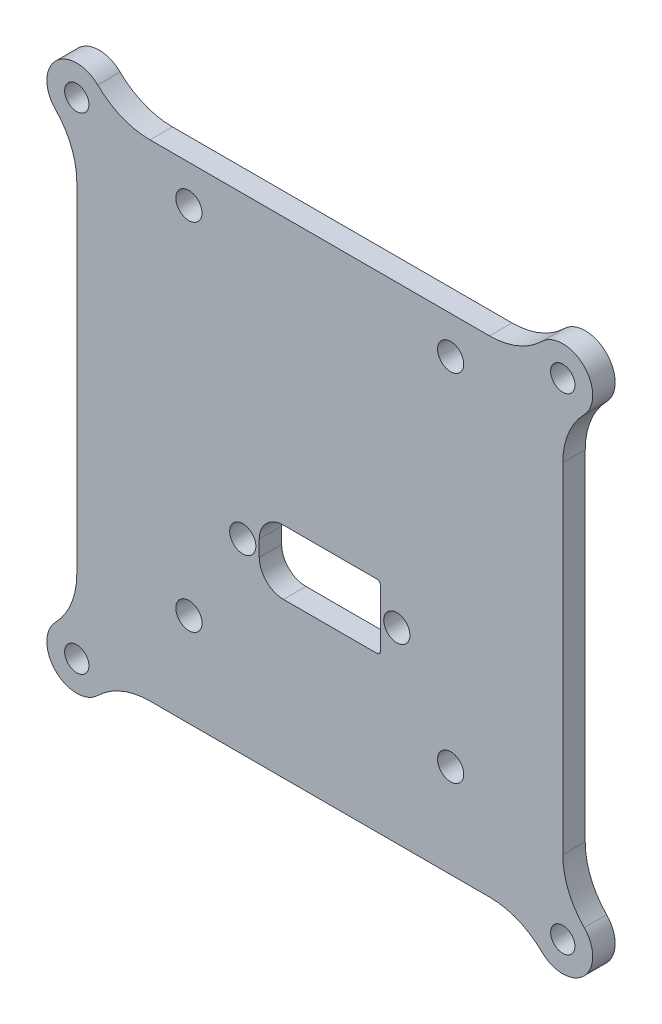
SolidWorks part; units mm, degrees
material "ABS"
ref_plane "Спереди" through (0, 0, 0) normal (0, 0, 1) x (1, 0, 0)
ref_plane "Сверху" through (0, 0, 0) normal (0, 1, 0) x (1, 0, 0)
ref_plane "Справа" through (0, 0, 0) normal (1, 0, 0) x (0, 0, -1)
sketch "Эскиз1" plane through (0, 0, 0) normal (0, 0, 1) x (1, 0, 0)
  line L1 (-32.5, -32.5) -> (32.5, -32.5)
  line L2 (-32.5, -32.5) -> (-32.5, 32.5)
  line L3 (-32.5, 32.5) -> (32.5, 32.5)
  line L4 (32.5, -32.5) -> (32.5, 32.5)
  line L5 (-32.5, -32.5) -> (32.5, 32.5) construction
  line L6 (-32.5, 32.5) -> (32.5, -32.5) construction
  circle A0 centre (-32.5, 32.5) radius 1.625
  arc A1 (-28.5, 32.5) -> (-32.5, 28.5) centre (-32.5, 32.5) ccw
  circle A2 centre (32.5, 32.5) radius 1.625
  arc A3 (32.5, 28.5) -> (28.5, 32.5) centre (32.5, 32.5) ccw
  circle A4 centre (32.5, -32.5) radius 1.625
  arc A5 (28.5, -32.5) -> (32.5, -28.5) centre (32.5, -32.5) ccw
  circle A6 centre (-32.5, -32.5) radius 1.625
  arc A7 (-32.5, -28.5) -> (-28.5, -32.5) centre (-32.5, -32.5) ccw
  point P0 (0, 0)
  point P20 (0, 0)
  dimension "D2" = 3.25
  dimension "D3" = 8
  dimension "D1" = 65
  dimension "D4" = 4
extrude "Бобышка-Вытянуть1" add sketch "Эскиз1" along normal blind 3 contours A6 L1 A4 L4 A2 L3 A0 L2 | L3 A1 L2 A0 | L4 A3 L3 A2 | L1 A5 L4 A4 | L2 A7 L1 A6
fillet "Скругление1" radius 10 8 edges at (-28.5, -32.5, 1.5) (-32.5, -28.5, 1.5) (-28.5, 32.5, 1.5) (-32.5, 28.5, 1.5) (28.5, 32.5, 1.5) (32.5, 28.5, 1.5) (32.5, -28.5, 1.5) (28.5, -32.5, 1.5)
sketch "Эскиз3" plane through (0, 0, 0) normal (0, 0, -1) x (-1, 0, 0)
  line L0 (0, 32.5) -> (0, -32.5) construction
  line L1 (22.702, 32.5) -> (-22.702, 32.5) construction
  line L2 (22.702, -32.5) -> (-22.702, -32.5) construction
  line L3 (-31.8936, 27.5) -> (26.7306, 27.5) construction
  circle A0 centre (-17.5, 27.5) radius 1.75
  circle A1 centre (17.5, 27.5) radius 1.75
  dimension "D1" = 3.5
  dimension "D2" = 17.5
  dimension "D3" = 27.5
extrude "Вырез-Вытянуть1" cut sketch "Эскиз3" against normal blind 10
sketch "Эскиз4" plane through (0, 0, 0) normal (0, 0, -1) x (-1, 0, 0)
  line L0 (0, 32.5) -> (0, -32.5) construction
  line L1 (22.702, 32.5) -> (-22.702, 32.5) construction
  line L2 (22.702, -32.5) -> (-22.702, -32.5) construction
  line L3 (-20.0878, -20) -> (30.9712, -20) construction
  circle A0 centre (-17.5, -20) radius 1.75
  circle A1 centre (17.5, -20) radius 1.75
  dimension "D1" = 3.5
  dimension "D2" = 17.5
  dimension "D3" = 20
extrude "Вырез-Вытянуть2" cut sketch "Эскиз4" against normal blind 10
sketch "Эскиз5" plane through (0, 0, 0) normal (0, 0, -1) x (-1, 0, 0)
  line L0 (0, 32.5) -> (0, -32.5) construction
  line L1 (22.702, 32.5) -> (-22.702, 32.5) construction
  line L2 (22.702, -32.5) -> (-22.702, -32.5) construction
  line L3 (-16.5784, -7.5) -> (15.5569, -7.5) construction
  circle A0 centre (-10.3, -7.5) radius 1.75
  circle A1 centre (10.3, -7.5) radius 1.75
  dimension "D1" = 3.5
  dimension "D2" = 20.6
  dimension "D3" = 7.5
extrude "Вырез-Вытянуть3" cut sketch "Эскиз5" against normal blind 10
sketch "Эскиз7" plane through (0, 0, 0) normal (0, 0, -1) x (-1, 0, 0)
  line L0 (-7.85, -3.65) -> (-7.85, -11.35)
  line L1 (-7.65, -3.45) -> (4.85, -3.45)
  line L2 (7.85, -6.45) -> (7.85, -8.55)
  line L3 (-7.65, -11.55) -> (4.85, -11.55)
  line L4 (-7.65, -3.2) -> (4.85, -3.2)
  line L5 (8.1, -6.45) -> (8.1, -8.55)
  line L6 (-7.65, -11.8) -> (4.85, -11.8)
  line L7 (-8.1, -3.65) -> (-8.1, -11.35)
  arc A0 (7.85, -6.45) -> (4.85, -3.45) centre (4.85, -6.45) ccw
  arc A1 (4.85, -11.55) -> (7.85, -8.55) centre (4.85, -8.55) ccw
  arc A2 (-7.65, -3.45) -> (-7.85, -3.65) centre (-7.65, -3.65) ccw
  arc A3 (-7.85, -11.35) -> (-7.65, -11.55) centre (-7.65, -11.35) ccw
  arc A4 (8.1, -6.45) -> (4.85, -3.2) centre (4.85, -6.45) ccw
  arc A5 (4.85, -11.8) -> (8.1, -8.55) centre (4.85, -8.55) ccw
  arc A6 (-8.1, -11.35) -> (-7.65, -11.8) centre (-7.65, -11.35) ccw
  arc A7 (-7.65, -3.2) -> (-8.1, -3.65) centre (-7.65, -3.65) ccw
  dimension "D1" = 0.25
extrude "Вырез-Вытянуть4" cut sketch "Эскиз7" against normal blind 10 contours L0 A3 L3 A1 L2 A0 L1 A2 | L4 A7 L7 A6 L6 A5 L5 A4 A3 L0 A2 L1 A0 L2 A1 L3
